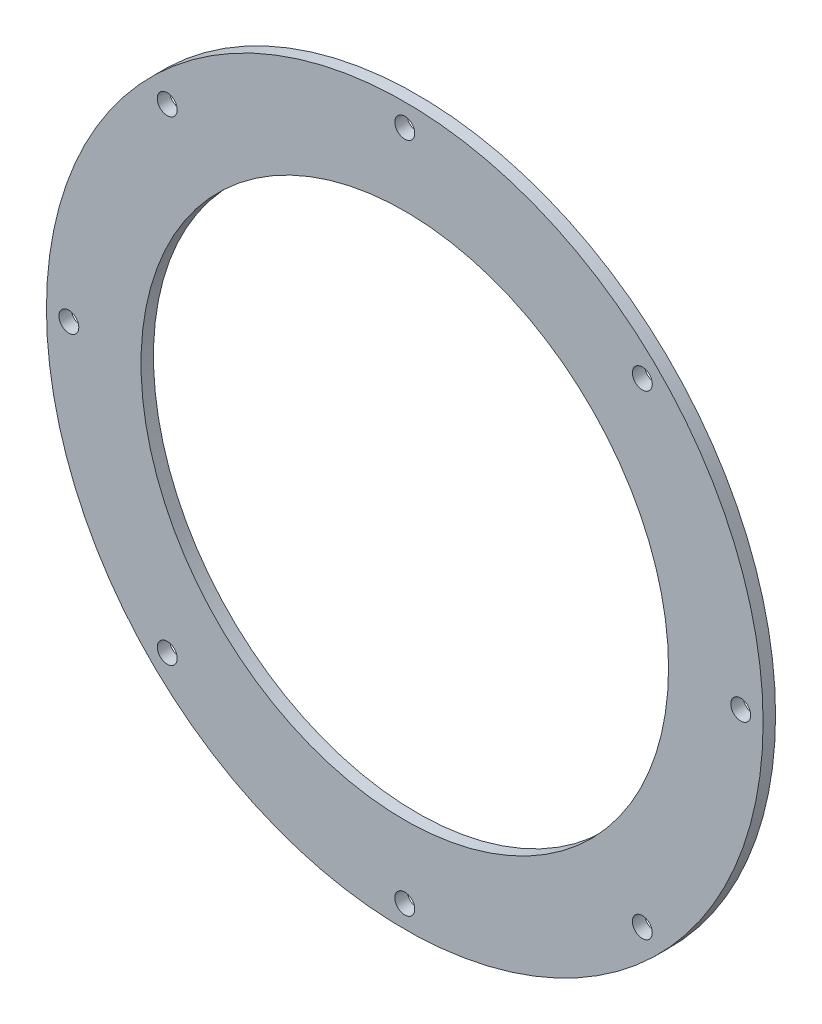
SolidWorks part; units mm, degrees
ref_plane "前视基准面" through (0, 0, 0) normal (0, 0, 1) x (1, 0, 0)
ref_plane "上视基准面" through (0, 0, 0) normal (0, 1, 0) x (1, 0, 0)
ref_plane "右视基准面" through (0, 0, 0) normal (1, 0, 0) x (0, 0, -1)
sketch "草图1" plane through (0, 0, 0) normal (0, 0, 1) x (1, 0, 0)
  circle A0 centre (0, 0) radius 67.5 construction
  circle A1 centre (0, -67.5) radius 2
  circle A2 centre (-47.7297, -47.7297) radius 2
  circle A3 centre (-67.5, 0) radius 2
  circle A4 centre (-47.7297, 47.7297) radius 2
  circle A5 centre (0, 67.5) radius 2
  circle A6 centre (47.7297, 47.7297) radius 2
  circle A7 centre (67.5, 0) radius 2
  circle A8 centre (47.7297, -47.7297) radius 2
  circle A9 centre (0, 0) radius 53
  circle A10 centre (0, 0) radius 72
  dimension "D1" = 135
  dimension "D2" = 8
  dimension "D3" = 144
  dimension "D4" = 106
extrude "凸台-拉伸1" add sketch "草图1" along normal blind 2.5
